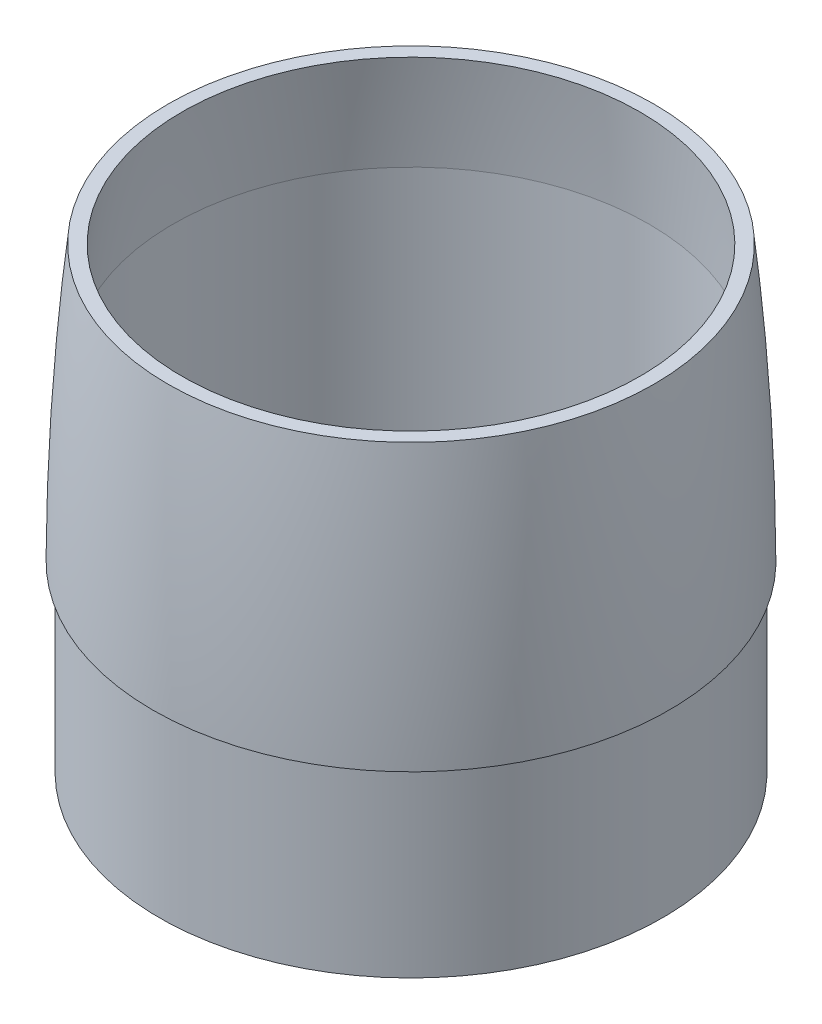
SolidWorks part; units mm, degrees
ref_plane "Front Plane" through (0, 0, 0) normal (0, 0, 1) x (1, 0, 0)
ref_plane "Top Plane" through (0, 0, 0) normal (0, 1, 0) x (1, 0, 0)
ref_plane "Right Plane" through (0, 0, 0) normal (1, 0, 0) x (0, 0, -1)
sketch "Croquis1" plane through (0, 0, 0) normal (1, 0, 0) x (0, 0, -1)
  line L0 (0, 0) -> (0, 290) construction
  line L1 (52, 10) -> (52, 77.802)
  line L3 (55, 40) -> (55, 0)
  line L4 (55, 0) -> (52, 0)
  line L5 (55, 40) -> (56.4, 40)
  line L6 (0, 290) -> (0, 282.8541)
  line L7 (52, 0) -> (0, 0)
  line L8 (0, 0) -> (0, 10)
  line L9 (0, 10) -> (52, 10)
  arc A0 (56.4, 40) -> (0, 290) centre (-539.2742, 36.9778) ccw
  arc A1 (52, 77.802) -> (0, 282.8541) centre (-539.2742, 36.9778) ccw
  arc A2 (53.4, 39.9848) -> (-2.7159, 288.7257) centre (-539.2742, 36.9778) ccw construction
  point P4 (0, 0)
  dimension "D7" = 595.6818
  dimension "D1" = 110
  dimension "D2" = 1.4
  dimension "D3" = 3
  dimension "D4" = 250
  dimension "D5" = 40
  dimension "D8" = 10
  dimension "D6" = 3
revolve "Revolución1" add sketch "Croquis1" angle 360 about L0
sketch "Croquis2" plane through (0, 0, 0) normal (1, 0, 0) x (0, 0, -1)
  line L0 (-55, 0) -> (55, 0) construction
  line L1 (-62.1083, 100) -> (60.9438, 100)
  line L2 (-62.1083, 100) -> (-62.1083, 321.261)
  line L3 (-62.1083, 321.261) -> (60.9438, 321.261)
  line L4 (60.9438, 100) -> (60.9438, 321.261)
  point P4 (0, 0)
  point P5 (60.9438, 78.2335)
  dimension "D1" = 100
extrude "Cortar-Extruir1" cut sketch "Croquis2" against normal through all both and the other way through all
equation "\"R\" = ( \"L\" ^ 2 + \"Rn\" ^ 2 ) / ( 2 * \"Rn\" )'2"
equation "\"D7@Croquis1\"=\"R\""
equation "\"L\"=250"
equation "\"D4@Croquis1\"=\"L\""
equation "\"Diameter\"=110"
equation "\"D1@Croquis1\"=\"Diameter\""
equation "\"Rn\"= \"Diameter\" / 2"
